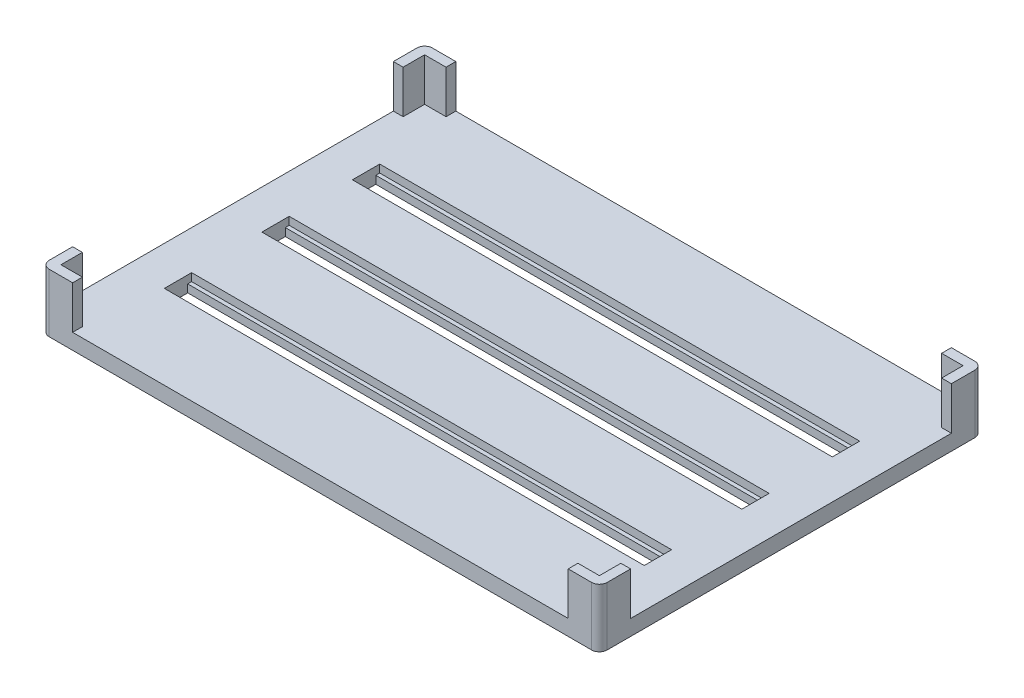
SolidWorks part; units mm, degrees
ref_plane "Front Plane" through (0, 0, 0) normal (0, 0, 1) x (1, 0, 0)
ref_plane "Top Plane" through (0, 0, 0) normal (0, 1, 0) x (1, 0, 0)
ref_plane "Right Plane" through (0, 0, 0) normal (1, 0, 0) x (0, 0, -1)
sketch "Sketch1" plane through (0, 0, 0) normal (0, 1, 0) x (1, 0, 0)
  line L1 (-69.5, -49.1) -> (69.5, -49.1)
  line L2 (-71.5, -47.1) -> (-71.5, 47.1)
  line L3 (-69.5, 49.1) -> (69.5, 49.1)
  line L4 (71.5, -47.1) -> (71.5, 47.1)
  line L5 (-71.5, -49.1) -> (71.5, 49.1) construction
  line L6 (-71.5, 49.1) -> (71.5, -49.1) construction
  arc A0 (69.5, -49.1) -> (71.5, -47.1) centre (69.5, -47.1) ccw
  arc A1 (-69.5, -49.1) -> (-71.5, -47.1) centre (-69.5, -47.1) cw
  arc A2 (69.5, 49.1) -> (71.5, 47.1) centre (69.5, 47.1) cw
  arc A3 (-71.5, 47.1) -> (-69.5, 49.1) centre (-69.5, 47.1) cw
  point P0 (0, 0)
  dimension "D3" = 2
  dimension "D1" = 143
  dimension "D2" = 98.2
extrude "Boss-Extrude1" add sketch "Sketch1" along normal blind 15
sketch "Sketch2" plane through (0, 15, 0) normal (0, 1, 0) x (1, 0, 0)
  line L1 (-69, -46.6) -> (69, -46.6)
  line L2 (-69, -46.6) -> (-69, 46.6)
  line L3 (-69, 46.6) -> (69, 46.6)
  line L4 (69, -46.6) -> (69, 46.6)
  line L5 (-69, -46.6) -> (69, 46.6) construction
  line L6 (-69, 46.6) -> (69, -46.6) construction
  point P0 (0, 0)
  dimension "D1" = 138
  dimension "D2" = 93.2
extrude "Cut-Extrude1" cut sketch "Sketch2" against normal blind 11
sketch "Sketch3" plane through (0, 15, 0) normal (0, 1, 0) x (1, 0, 0)
  line L0 (0, 56.4331) -> (0, -61.1236) construction
  line L1 (-87.5079, 0) -> (105.3906, 0) construction
  line L2 (-71.5, 47.1) -> (-71.5, -47.1) construction
  line L3 (-71.5, 41.1) -> (-69, 41.1)
  line L4 (-71.5, 41.1) -> (-71.5, -41.1)
  line L5 (-71.5, -41.1) -> (-69, -41.1)
  line L6 (-69, 41.1) -> (-69, -41.1)
  line L7 (-69, 46.6) -> (-69, -46.6) construction
  line L8 (69.5, 49.1) -> (-69.5, 49.1) construction
  line L9 (-69.5, -49.1) -> (69.5, -49.1) construction
  line L10 (69, 46.6) -> (-69, 46.6) construction
  line L11 (-63.5, 49.1) -> (63.5, 49.1)
  line L12 (-63.5, 49.1) -> (-63.5, 46.6)
  line L13 (-63.5, 46.6) -> (63.5, 46.6)
  line L14 (63.5, 49.1) -> (63.5, 46.6)
  line L15 (71.5, -47.1) -> (71.5, 47.1) construction
  line L16 (71.5, -41.1) -> (69, -41.1)
  line L17 (69, 41.1) -> (69, -41.1)
  line L18 (71.5, 41.1) -> (69, 41.1)
  line L19 (71.5, 41.1) -> (71.5, -41.1)
  line L20 (-63.5, -46.6) -> (63.5, -46.6)
  line L21 (63.5, -49.1) -> (63.5, -46.6)
  line L22 (-63.5, -49.1) -> (63.5, -49.1)
  line L23 (-63.5, -49.1) -> (-63.5, -46.6)
  dimension "D1" = 8
  dimension "D2" = 8
  dimension "D3" = 8
  dimension "D4" = 8
extrude "Cut-Extrude2" cut sketch "Sketch3" against normal blind 11
sketch "Sketch7" plane through (0, 4, 0) normal (0, 1, 0) x (1, 0, 0)
  line L0 (-71.5, 24.1) -> (71.5, 24.1) construction
  line L1 (-71.5, 41.1) -> (-71.5, -41.1) construction
  line L2 (71.5, -41.1) -> (71.5, 41.1) construction
  line L3 (-71.5, -24.1) -> (71.5, -24.1) construction
  line L4 (63.5, 49.1) -> (-63.5, 49.1) construction
  line L5 (-63.5, -49.1) -> (63.5, -49.1) construction
  line L6 (-61.5, -2.6) -> (-61.5, 4.4)
  line L7 (-61.5, 20.6) -> (61.5, 20.6)
  line L8 (-61.5, 20.6) -> (-61.5, 27.6)
  line L9 (-61.5, 27.6) -> (61.5, 27.6)
  line L10 (61.5, 20.6) -> (61.5, 27.6)
  line L11 (-61.5, 20.6) -> (61.5, 27.6) construction
  line L12 (-61.5, 27.6) -> (61.5, 20.6) construction
  line L13 (-61.5, -27.6) -> (61.5, -27.6)
  line L14 (-61.5, -27.6) -> (-61.5, -20.6)
  line L15 (-61.5, -20.6) -> (61.5, -20.6)
  line L16 (61.5, -27.6) -> (61.5, -20.6)
  line L17 (-61.5, -27.6) -> (61.5, -20.6) construction
  line L18 (-61.5, -20.6) -> (61.5, -27.6) construction
  line L19 (-61.5, -2.6) -> (61.5, -2.6)
  line L20 (61.5, -2.6) -> (61.5, 4.4)
  line L21 (-61.5, 4.4) -> (61.5, 4.4)
  point P12 (0, 24.1)
  point P17 (0, -24.1)
  dimension "D1" = 25
  dimension "D2" = 25
  dimension "D3" = 7
  dimension "D4" = 123
  dimension "D5" = 7
  dimension "D6" = 123
  dimension "D7" = 2
extrude "Cut-Extrude6" cut sketch "Sketch7" against normal blind 2
sketch "Sketch8" plane through (0, 2, 0) normal (0, 1, 0) x (1, 0, 0)
  line L0 (-61.5, 24.1) -> (61.5, 24.1) construction
  line L1 (-61.5, 27.6) -> (-61.5, 20.6) construction
  line L2 (61.5, 20.6) -> (61.5, 27.6) construction
  line L3 (-61.5, -24.1) -> (61.5, -24.1) construction
  line L4 (-61.5, -20.6) -> (-61.5, -27.6) construction
  line L5 (61.5, -27.6) -> (61.5, -20.6) construction
  line L6 (-61.5, -1.6) -> (-61.5, 3.4)
  line L7 (-61.5, 21.6) -> (61.5, 21.6)
  line L8 (-61.5, 21.6) -> (-61.5, 26.6)
  line L9 (-61.5, 26.6) -> (61.5, 26.6)
  line L10 (61.5, 21.6) -> (61.5, 26.6)
  line L11 (-61.5, 21.6) -> (61.5, 26.6) construction
  line L12 (-61.5, 26.6) -> (61.5, 21.6) construction
  line L13 (-61.5, -26.6) -> (61.5, -26.6)
  line L14 (-61.5, -26.6) -> (-61.5, -21.6)
  line L15 (-61.5, -21.6) -> (61.5, -21.6)
  line L16 (61.5, -26.6) -> (61.5, -21.6)
  line L17 (-61.5, -26.6) -> (61.5, -21.6) construction
  line L18 (-61.5, -21.6) -> (61.5, -26.6) construction
  line L19 (-61.5, -1.6) -> (61.5, -1.6)
  line L20 (61.5, -1.6) -> (61.5, 3.4)
  line L21 (-61.5, 3.4) -> (61.5, 3.4)
  point P12 (0, 24.1)
  point P17 (0, -24.1)
  dimension "D1" = 5
  dimension "D2" = 5
  dimension "D3" = 2
extrude "Cut-Extrude7" cut sketch "Sketch8" against normal blind 10
